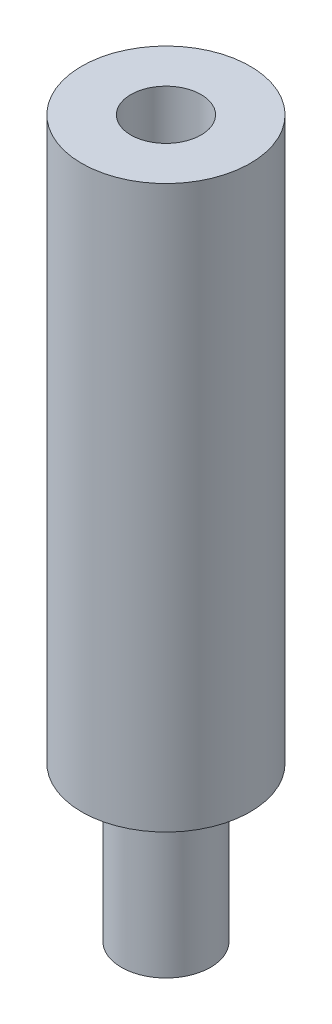
SolidWorks part; units mm, degrees
material "Silicon Rubber"
ref_plane "Front" through (0, 0, 0) normal (0, 0, 1) x (1, 0, 0)
ref_plane "Top" through (0, 0, 0) normal (0, 1, 0) x (1, 0, 0)
ref_plane "Right" through (0, 0, 0) normal (1, 0, 0) x (0, 0, -1)
sketch "Sketch1" plane through (0, 0, 0) normal (0, 1, 0) x (1, 0, 0)
  circle A0 centre (0, 0) radius 1.5875
  circle A1 centre (0, 0) radius 0.5
  dimension "D1" = 3.175
  dimension "D2" = 1
extrude "Boss-Extrude1" add sketch "Sketch1" along normal blind 5.5
ref_plane "Plane1" through (0, 5.25, 0) normal (0, -1, 0) x (-1, 0, 0)
sketch "Sketch2" plane through (0, 5.25, 0) normal (0, -1, 0) x (-1, 0, 0)
  circle A0 centre (0, 0) radius 2
  circle A1 centre (0, 0) radius 1.5875
  circle A2 centre (0, 0) radius 1.5875 construction
  dimension "D1" = 4
extrude "Boss-Extrude2" add sketch "Sketch2" against normal blind 0.25
sketch "Sketch3" plane through (0, 5.5, 0) normal (0, 1, 0) x (1, 0, 0)
  circle A0 centre (0, 0) radius 3
  circle A1 centre (0, 0) radius 0.5
  circle A2 centre (0, 0) radius 0.5 construction
  dimension "D1" = 6
extrude "Boss-Extrude3" add sketch "Sketch3" along normal blind 20
sketch "Sketch4" plane through (0, 25.5, 0) normal (0, 1, 0) x (1, 0, 0)
  circle A0 centre (0, 0) radius 1.25
  dimension "D1" = 2.5
extrude "Cut-Extrude1" cut sketch "Sketch4" against normal blind 10
